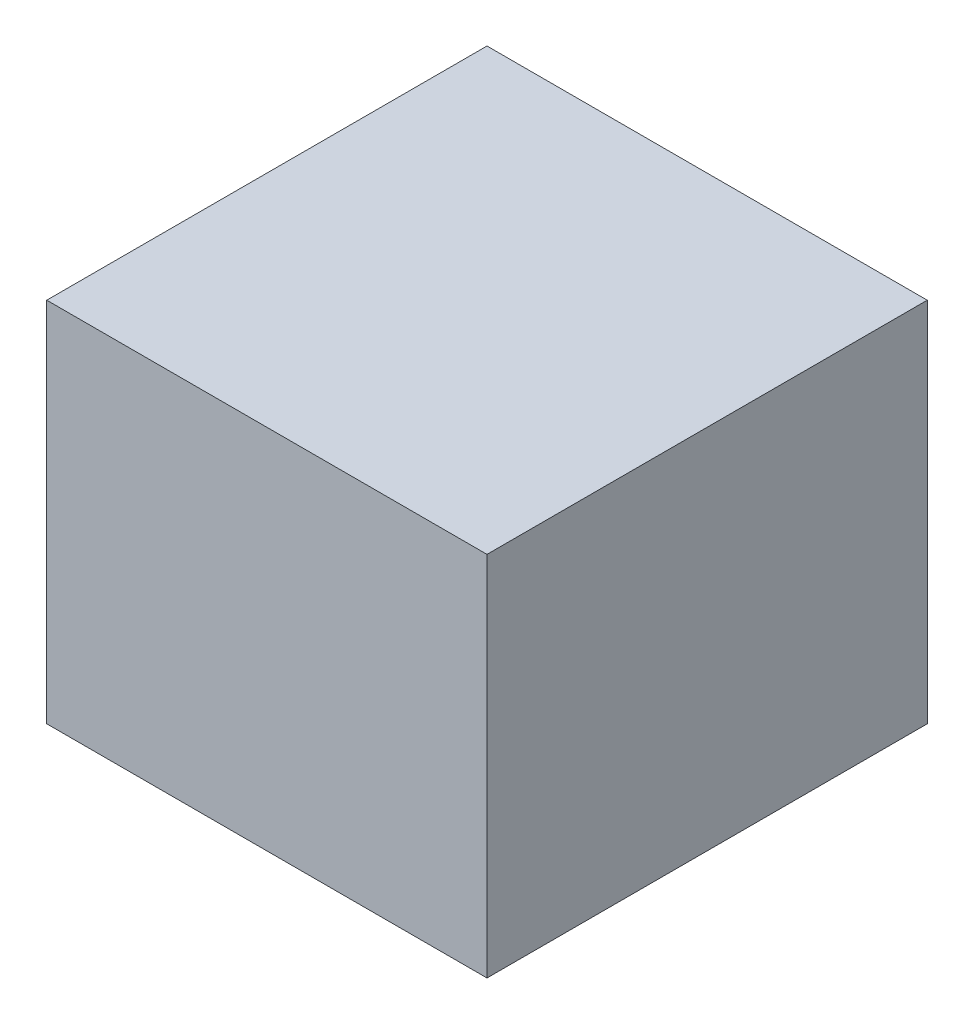
SolidWorks part; units mm, degrees
material "PBT General Purpose"
ref_plane "Front Plane" through (0, 0, 0) normal (0, 0, 1) x (1, 0, 0)
ref_plane "Top Plane" through (0, 0, 0) normal (0, 1, 0) x (1, 0, 0)
ref_plane "Right Plane" through (0, 0, 0) normal (1, 0, 0) x (0, 0, -1)
sketch "Sketch1" plane through (0, 0, 0) normal (0, 0, 1) x (1, 0, 0)
  line L1 (0, 0) -> (76.2, 0)
  line L2 (0, 0) -> (0, 63.5)
  line L3 (0, 63.5) -> (76.2, 63.5)
  line L4 (76.2, 0) -> (76.2, 63.5)
  dimension "D1" = 76.2
  dimension "D2" = 63.5
extrude "Boss-Extrude1" add sketch "Sketch1" along normal blind 76.2
ref_plane "Plane1" through (0, 0, 38.1) normal (0, 0, 1) x (1, 0, 0)
